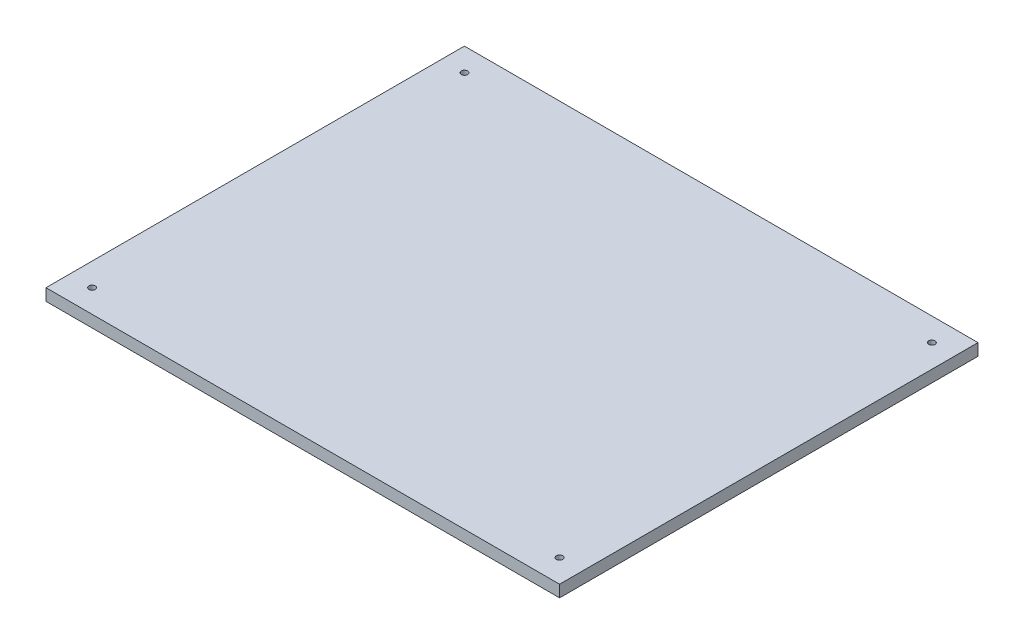
SolidWorks part; units mm, degrees
material "Acrylic (Medium-high impact)"
ref_plane "Front Plane" through (0, 0, 0) normal (0, 0, 1) x (1, 0, 0)
ref_plane "Top Plane" through (0, 0, 0) normal (0, 1, 0) x (1, 0, 0)
ref_plane "Right Plane" through (0, 0, 0) normal (1, 0, 0) x (0, 0, -1)
sketch "Sketch1" plane through (0, 0, 0) normal (0, 1, 0) x (1, 0, 0)
  line L1 (-137.3886, 111.9378) -> (137.3886, 111.9378)
  line L2 (-137.3886, 111.9378) -> (-137.3886, -111.9378)
  line L3 (-137.3886, -111.9378) -> (137.3886, -111.9378)
  line L4 (137.3886, 111.9378) -> (137.3886, -111.9378)
  line L5 (-137.3886, 111.9378) -> (137.3886, -111.9378) construction
  line L6 (-137.3886, -111.9378) -> (137.3886, 111.9378) construction
  point P0 (0, 0)
  dimension "D1" = 223.8756
  dimension "D2" = 274.7772
extrude "Boss-Extrude1" add sketch "Sketch1" along normal blind 6.35
hole_wizard "M3 Clearance Hole1" positions "Sketch2" profile "Sketch3" hole size "M3" standard "ANSI Metric" end condition through all
sketch "Sketch2" plane through (0, 6.35, 0) normal (0, 1, 0) x (1, 0, 0)
  line L0 (-137.3886, -111.9378) -> (137.3886, -111.9378) construction
  line L1 (137.3886, -111.9378) -> (137.3886, 111.9378) construction
  line L2 (137.3886, 111.9378) -> (-137.3886, 111.9378) construction
  line L3 (-137.3886, 111.9378) -> (-137.3886, -111.9378) construction
  point P0 (125.0442, -99.5934)
  point P2 (-125.0442, -99.5934)
  point P4 (-125.0442, 99.5934)
  point P6 (125.0442, 99.5934)
  point P17 (0, 0)
  point P18 (0, 0)
  point P19 (0, 0)
  point P20 (0, 0)
  dimension "D1" = 12.3444
  dimension "D2" = 12.3444
  dimension "D3" = 12.3444
  dimension "D4" = 12.3444
sketch "Sketch3" plane through (125.0442, 6.35, 99.5934) normal (1, 0, 0) x (0, 0, 1)
  line L0 (0, 0) -> (0, 6.35)
  line L1 (0, 6.35) -> (1.7, 6.35)
  line L2 (1.7, 6.35) -> (1.7, 0)
  line L5 (1.7, 0) -> (0, 0)
  line L11 (0, -6.35) -> (0, 107.95) construction
  dimension "Thru Hole Dia." = 3.4
  dimension "Thru Hole Depth" = 6.35
